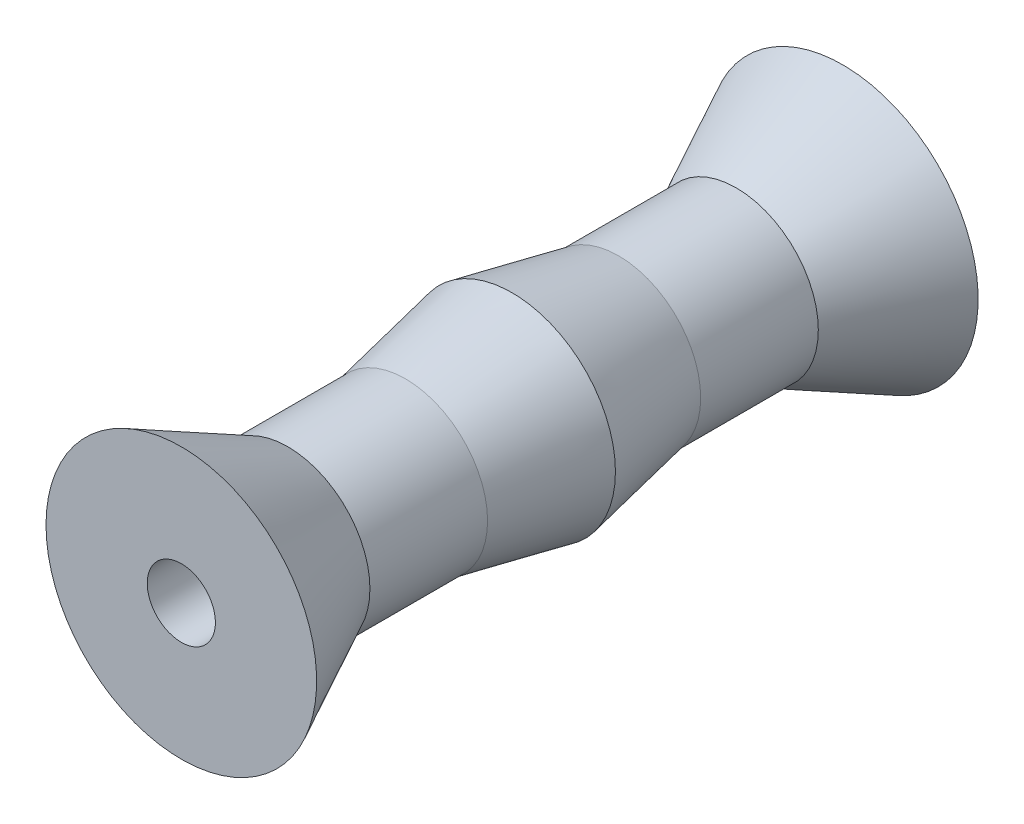
SolidWorks part; units mm, degrees
ref_plane "Plan de face" through (0, 0, 0) normal (0, 0, 1) x (1, 0, 0)
ref_plane "Plan de dessus" through (0, 0, 0) normal (0, 1, 0) x (1, 0, 0)
ref_plane "Plan de droite" through (0, 0, 0) normal (1, 0, 0) x (0, 0, -1)
sketch "Esquisse1" plane through (0, 0, 0) normal (0, 0, 1) x (1, 0, 0)
  circle A1 centre (0, 0) radius 2.032
  circle A2 centre (0, 0) radius 4.8895
  dimension "D1" = 4.064
  dimension "D2" = 2.8575
extrude "Boss.-Extru.1" add sketch "Esquisse1" along normal mid plane 39.42
sketch "Esquisse2" plane through (0, 0, 0) normal (1, 0, 0) x (0, 0, -1)
  line L0 (-13.36, 4.8895) -> (-19.71, 8.0645)
  line L1 (19.71, 4.8895) -> (-19.71, 4.8895) construction
  line L2 (-19.71, 8.0645) -> (-19.71, 4.8895)
  line L3 (-19.71, 4.8895) -> (-13.36, 4.8895)
  line L5 (0, 6.1595) -> (-6.35, 4.8895)
  line L6 (-6.35, 4.8895) -> (0, 4.8895)
  line L7 (0, 0) -> (-19.71, 0) construction
  line L8 (-19.71, 4.8895) -> (-19.71, -4.8895) construction
  line L9 (19.71, 4.8895) -> (19.71, 8.0645)
  line L10 (19.71, 8.0645) -> (13.36, 4.8895)
  line L11 (13.36, 4.8895) -> (19.71, 4.8895)
  line L12 (0, 4.8895) -> (6.35, 4.8895)
  line L13 (6.35, 4.8895) -> (0, 6.1595)
  line L14 (0, 0) -> (19.71, 0) construction
  line L15 (19.71, -4.8895) -> (19.71, 4.8895) construction
  dimension "D1" = 3.175
  dimension "D2" = 6.35
  dimension "D3" = 6.35
  dimension "D4" = 1.27
  dimension "D5" = 6.35
  dimension "D6" = 6.35
  dimension "D7" = 3.175
  dimension "D8" = 1.27
revolve "Révolution1" add sketch "Esquisse2" angle 360 about L7
